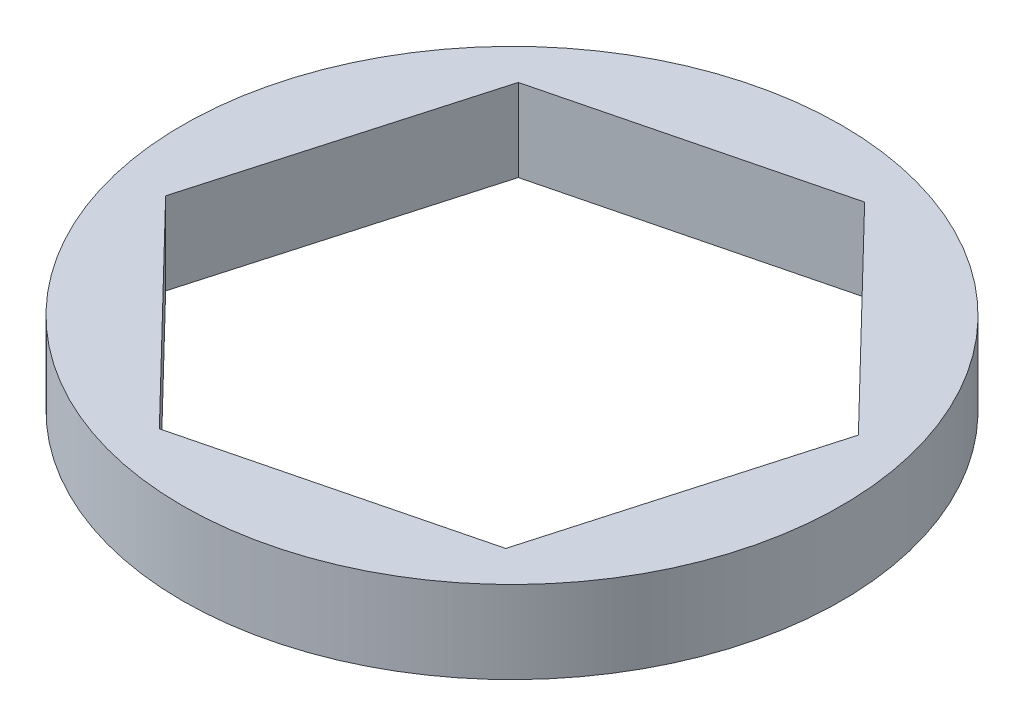
SolidWorks part; units mm, degrees
ref_plane "Front Plane" through (0, 0, 0) normal (0, 0, 1) x (1, 0, 0)
ref_plane "Top Plane" through (0, 0, 0) normal (0, 1, 0) x (1, 0, 0)
ref_plane "Right Plane" through (0, 0, 0) normal (1, 0, 0) x (0, 0, -1)
sketch "Sketch1" plane through (0, 0, 0) normal (0, 1, 0) x (1, 0, 0)
  line L1 (1.5057, 5.2891) -> (-3.8277, 3.9485)
  line L2 (-3.8277, 3.9485) -> (-5.3333, -1.3406)
  line L3 (-5.3333, -1.3406) -> (-1.5057, -5.2891)
  line L4 (-1.5057, -5.2891) -> (3.8277, -3.9485)
  line L5 (3.8277, -3.9485) -> (5.3333, 1.3406)
  line L6 (5.3333, 1.3406) -> (1.5057, 5.2891)
  circle A0 centre (0, 0) radius 4.7625 construction
  circle A1 centre (0, 0) radius 6.35
  dimension "D2" = 12.7
  dimension "D1" = 9.525
extrude "Boss-Extrude1" add sketch "Sketch1" along normal blind 1.5875
